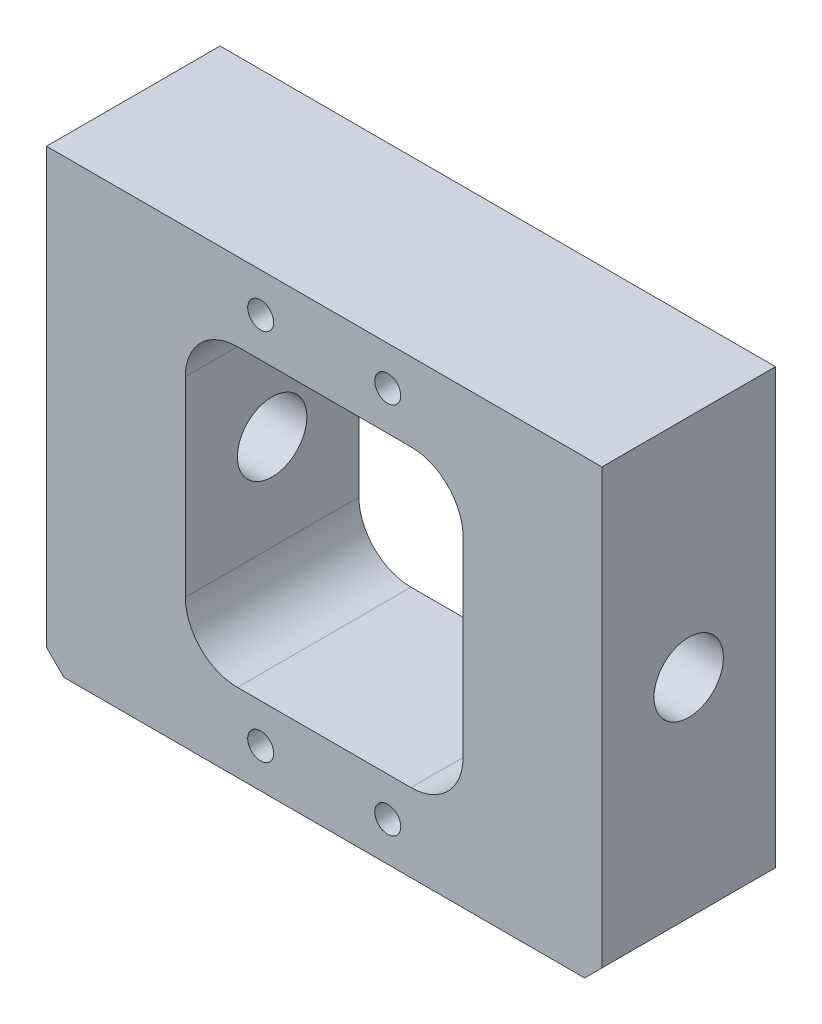
SolidWorks part; units mm, degrees
ref_plane "Спереди" through (0, 0, 0) normal (0, 0, 1) x (1, 0, 0)
ref_plane "Сверху" through (0, 0, 0) normal (0, 1, 0) x (1, 0, 0)
ref_plane "Справа" through (0, 0, 0) normal (1, 0, 0) x (0, 0, -1)
sketch "Эскиз1" plane through (0, 0, 0) normal (0, 0, 1) x (1, 0, 0)
  line L1 (-16, 13) -> (16, 13)
  line L2 (-16, 13) -> (-16, -13)
  line L3 (-16, -13) -> (16, -13)
  line L4 (16, 13) -> (16, -13)
  line L5 (-16, 13) -> (16, -13) construction
  line L6 (-16, -13) -> (16, 13) construction
  point P0 (0, 0)
extrude "Вытянуть1" add sketch "Эскиз1" along normal blind 10
sketch "Эскиз2" plane through (0, 0, 10) normal (0, 0, 1) x (1, 0, 0)
  line L0 (0, -19.2449) -> (0, 23.2707) construction
  line L2 (0, 0) -> (36.31, 0) construction
  line L4 (-8, 8.5) -> (8, 8.5)
  line L5 (-8, 8.5) -> (-8, -8.5)
  line L6 (-8, -8.5) -> (8, -8.5)
  line L7 (8, 8.5) -> (8, -8.5)
  line L8 (-8, 8.5) -> (8, -8.5) construction
  line L9 (-8, -8.5) -> (8, 8.5) construction
  point P2 (0, 0)
extrude "Вытянуть2" cut sketch "Эскиз2" against normal through all
fillet "Скругление1" radius 3 4 edges at (8, -8.5, 5) (8, 8.5, 5) (-8, 8.5, 5) (-8, -8.5, 5)
sketch "Эскиз3" plane through (-16, 0, 0) normal (-1, 0, 0) x (0, 0, 1)
  line L0 (10, 0) -> (25.7128, 0) construction
  line L2 (5, 19.2449) -> (5, 11.0914) construction
  circle A0 centre (5, 0) radius 2
extrude "Вытянуть3" cut sketch "Эскиз3" against normal through all
chamfer "Фаска1" distance 1 angle 45 2 edges at (16, -13, 5) (-16, -13, 5)
sketch "Эскиз4" plane through (0, 0, 0) normal (0, 0, -1) x (-1, 0, 0)
  line L0 (0, 11.683) -> (0, 17.5017) construction
  line L1 (16.5, 0) -> (30.3798, 0) construction
  line L4 (5.2102, 10.75) -> (2.6268, 10.75) construction
  circle A0 centre (-3.66, 10.75) radius 0.75
  circle A1 centre (3.66, 10.75) radius 0.75
  circle A2 centre (3.66, -10.75) radius 0.75
  circle A3 centre (-3.66, -10.75) radius 0.75
  dimension "D1" = 3.66
extrude "Вырез-Вытянуть1" cut sketch "Эскиз4" against normal through all
